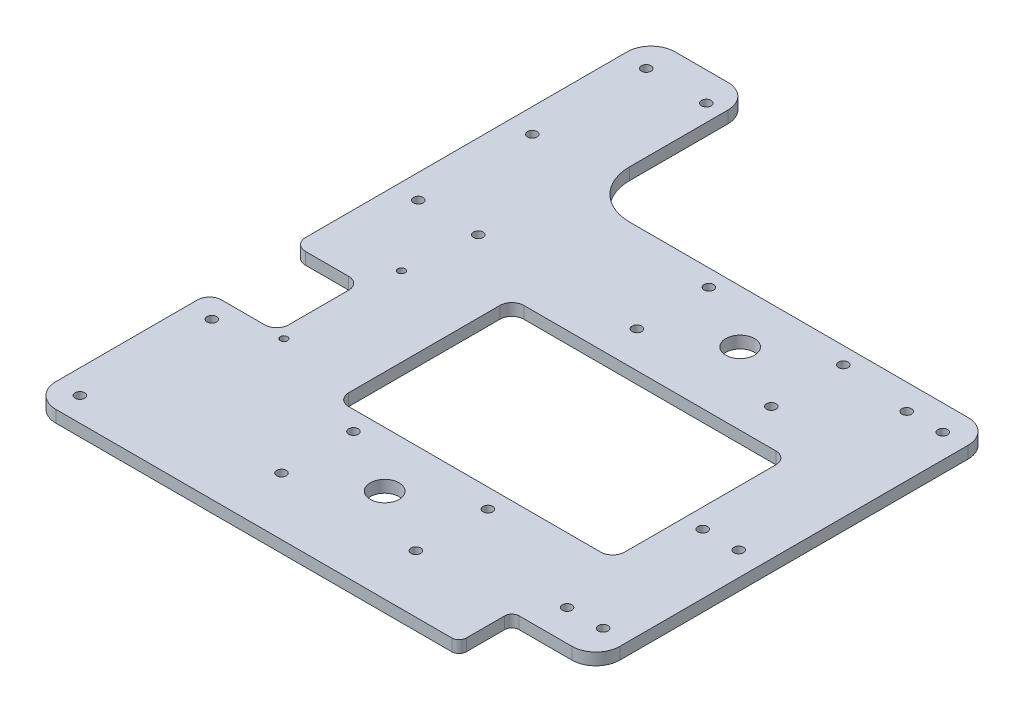
SolidWorks part; units mm, degrees
ref_plane "前视基准面" through (0, 0, 0) normal (0, 0, 1) x (1, 0, 0)
ref_plane "上视基准面" through (0, 0, 0) normal (0, 1, 0) x (1, 0, 0)
ref_plane "右视基准面" through (0, 0, 0) normal (1, 0, 0) x (0, 0, -1)
sketch "草图1" plane through (0, 0, 0) normal (0, 1, 0) x (1, 0, 0)
  line L1 (106.5, -100) -> (-106.5, -100)
  line L2 (106.5, -100) -> (106.5, 100)
  line L3 (106.5, 100) -> (-106.5, 100)
  line L4 (-106.5, -100) -> (-106.5, 100)
  line L5 (106.5, -100) -> (-106.5, 100) construction
  line L6 (106.5, 100) -> (-106.5, -100) construction
  point P0 (0, 0)
  dimension "D1" = 213
  dimension "D2" = 200
extrude "凸台-拉伸1" add sketch "草图1" along normal blind 5
sketch "草图2" plane through (0, 5, 0) normal (0, 1, 0) x (1, 0, 0)
  line L2 (106.5, 100) -> (-106.5, 100) construction
  line L4 (-106.5, 100) -> (-106.5, -100) construction
  circle A0 centre (-4.5, 93) radius 2
  circle A1 centre (51.5, 93) radius 2
  circle A2 centre (-4.5, 63) radius 2
  circle A3 centre (51.5, 63) radius 2
  circle A4 centre (-26.5, -33.0952) radius 2
  circle A5 centre (29.5, -33.0952) radius 2
  circle A6 centre (29.5, -63.0952) radius 2
  circle A7 centre (-26.5, -63.0952) radius 2
  circle A8 centre (1.5, -48.0952) radius 6
  circle A9 centre (23.5, 78) radius 6
  dimension "D2" = 28
  dimension "D3" = 56
  dimension "D4" = 56
  dimension "D5" = 15
  dimension "D6" = 30
  dimension "D7" = 15
  dimension "D8" = 30
  dimension "D9" = 4
  dimension "D10" = 4
  dimension "D11" = 4
  dimension "D12" = 4
  dimension "D13" = 4
  dimension "D14" = 4
  dimension "D15" = 4
  dimension "D16" = 4
  dimension "D17" = 56
  dimension "D18" = 56
  dimension "D19" = 30
  dimension "D20" = 30
  dimension "D21" = 28
  dimension "D22" = 15
  dimension "D23" = 12
  dimension "D24" = 12
  dimension "D25" = 22
  dimension "D26" = 108
  dimension "D27" = 128
  dimension "D28" = 130
  dimension "D29" = 28
  dimension "D30" = 28
  dimension "D31" = 15
extrude "切除-拉伸1" cut sketch "草图2" against normal through all
sketch "草图3" plane through (0, 5, 0) normal (0, 1, 0) x (1, 0, 0)
  line L0 (-106.5, -87.0952) -> (106.5, -87.0952)
  line L1 (-106.5, 100) -> (-106.5, -100) construction
  line L2 (106.5, -100) -> (106.5, 100) construction
  line L3 (106.5, -87.0952) -> (106.5, -100)
  line L4 (106.5, -100) -> (-106.5, -100)
  line L5 (-106.5, -100) -> (-106.5, -87.0952)
  circle A0 centre (1.5, -48.0952) radius 6 construction
  dimension "D1" = 39
extrude "切除-拉伸2" cut sketch "草图3" against normal through all
sketch "草图4" plane through (0, 5, 0) normal (0, 1, 0) x (1, 0, 0)
  line L0 (-106.5, 21.9048) -> (-78.5, 21.9048)
  line L1 (-106.5, 100) -> (-106.5, -87.0952) construction
  line L2 (-78.5, 21.9048) -> (-78.5, -13.0952)
  line L3 (-78.5, -13.0952) -> (-106.5, -13.0952)
  line L4 (-106.5, -13.0952) -> (-106.5, 21.9048)
  line L5 (106.5, -87.0952) -> (-106.5, -87.0952) construction
  dimension "D1" = 74
  dimension "D2" = 109
  dimension "D3" = 28
extrude "切除-拉伸3" cut sketch "草图4" against normal through all
fillet "圆角1" radius 5 4 edges at (-106.5, 2.5, 13.0952) (-78.5, 2.5, 13.0952) (-78.5, 2.5, -21.9048) (-106.5, 2.5, -21.9048)
sketch "草图5" plane through (0, 5, 0) normal (0, 1, 0) x (1, 0, 0)
  line L0 (-106.5, 100) -> (-106.5, 170.9048)
  line L1 (-106.5, 170.9048) -> (-64.5, 170.9048)
  line L2 (-64.5, 170.9048) -> (-64.5, 100)
  line L3 (106.5, 100) -> (-106.5, 100) construction
  line L4 (-106.5, 100) -> (-64.5, 100)
  line L5 (106.5, -87.0952) -> (-106.5, -87.0952) construction
  dimension "D1" = 258
  dimension "D2" = 42
extrude "凸台-拉伸2" add sketch "草图5" against normal blind 5
fillet "圆角2" radius 20 1 edges at (-64.5, 2.5, -100)
sketch "草图6" plane through (0, 5, 0) normal (0, 1, 0) x (1, 0, 0)
  line L0 (-64.5, 170.9048) -> (-106.5, 170.9048) construction
  line L1 (-106.5, 170.9048) -> (-106.5, 26.9048) construction
  circle A0 centre (-96.5, 158.9048) radius 2
  circle A1 centre (-71.5, 158.9048) radius 2
  circle A2 centre (-71.5, 63.9048) radius 2
  circle A3 centre (-96.5, 63.9048) radius 2
  dimension "D1" = 12
  dimension "D2" = 12
  dimension "D3" = 4
  dimension "D4" = 10
  dimension "D5" = 25
  dimension "D6" = 10
  dimension "D7" = 25
  dimension "D8" = 95
  dimension "D9" = 95
  dimension "D10" = 4
  dimension "D11" = 4
  dimension "D12" = 4
extrude "切除-拉伸4" cut sketch "草图6" against normal through all
sketch "草图7" plane through (0, 5, 0) normal (0, 1, 0) x (1, 0, 0)
  line L0 (-106.5, 170.9048) -> (-106.5, 26.9048) construction
  line L1 (-106.5, -18.0952) -> (-106.5, -87.0952) construction
  line L2 (106.5, -87.0952) -> (106.5, 100) construction
  line L3 (106.5, -87.0952) -> (-106.5, -87.0952) construction
  circle A0 centre (-96.5, 111.4048) radius 2
  circle A1 centre (-96.5, -22.0952) radius 2
  circle A2 centre (-96.5, -77.0952) radius 2
  circle A3 centre (96.5, -52.0952) radius 2
  circle A4 centre (96.5, 4.4048) radius 2
  circle A5 centre (96.5, 89.4048) radius 2
  circle A6 centre (81.5, 89.4048) radius 2
  circle A7 centre (81.5, 4.4048) radius 2
  circle A8 centre (81.5, -52.0952) radius 2
  dimension "D1" = 10
  dimension "D2" = 10
  dimension "D3" = 10
  dimension "D4" = 10
  dimension "D5" = 10
  dimension "D6" = 10
  dimension "D7" = 25
  dimension "D8" = 25
  dimension "D9" = 25
  dimension "D10" = 10
  dimension "D11" = 65
  dimension "D12" = 198.5
  dimension "D13" = 35
  dimension "D14" = 35
  dimension "D15" = 91.5
  dimension "D16" = 91.5
  dimension "D17" = 176.5
  dimension "D18" = 176.5
  dimension "D19" = 4
  dimension "D20" = 4
  dimension "D21" = 4
  dimension "D22" = 4
  dimension "D23" = 4
  dimension "D24" = 4
  dimension "D25" = 4
  dimension "D26" = 4
  dimension "D27" = 4
extrude "切除-拉伸5" cut sketch "草图7" against normal through all
sketch "草图8" plane through (0, 5, 0) normal (0, 1, 0) x (1, 0, 0)
  line L0 (71.5, -87.0952) -> (71.5, -65.0952)
  line L1 (106.5, -87.0952) -> (-106.5, -87.0952) construction
  line L2 (71.5, -65.0952) -> (91.5, -65.0952)
  line L3 (91.5, -65.0952) -> (91.5, -87.0952)
  line L4 (91.5, -87.0952) -> (71.5, -87.0952)
  line L9 (106.5, -87.0952) -> (106.5, 100) construction
  dimension "D1" = 22
  dimension "D4" = 15
  dimension "D5" = 20
extrude "切除-拉伸6" cut sketch "草图8" against normal through all
fillet "圆角3" radius 3 4 edges at (71.5, 2.5, 87.0952) (91.5, 2.5, 87.0952) (91.5, 2.5, 65.0952) (71.5, 2.5, 65.0952)
sketch "草图9" plane through (0, 5, 0) normal (0, 1, 0) x (1, 0, 0)
  line L0 (88.5, -65.0952) -> (106.5, -65.0952)
  line L1 (106.5, -87.0952) -> (106.5, 100) construction
  line L2 (106.5, -65.0952) -> (106.5, -87.0952)
  line L3 (106.5, -87.0952) -> (88.5, -87.0952)
  line L4 (88.5, -87.0952) -> (88.5, -65.0952)
extrude "切除-拉伸7" cut sketch "草图9" against normal through all
sketch "草图10" plane through (0, 5, 0) normal (0, 1, 0) x (1, 0, 0)
  line L0 (-106.5, -18.0952) -> (-106.5, -87.0952) construction
  line L1 (-106.5, 170.9048) -> (-106.5, 26.9048) construction
  line L5 (-83.5, 21.9048) -> (-101.5, 21.9048) construction
  circle A0 centre (-74.5, 34.9048) radius 1.5
  circle A1 centre (-74.5, -14.0952) radius 1.5
  dimension "D1" = 49
  dimension "D2" = 32
  dimension "D3" = 32
  dimension "D4" = 36
  dimension "D5" = 3
  dimension "D6" = 3
extrude "切除-拉伸8" cut sketch "草图10" against normal through all
fillet "圆角4" radius 10 5 edges at (-106.5, 2.5, 87.0952) (-106.5, 2.5, -170.9048) (-64.5, 2.5, -170.9048) (106.5, 2.5, -100) (106.5, 2.5, 65.0952)
sketch "草图11" plane through (0, 5, 0) normal (0, 1, 0) x (1, 0, 0)
  line L0 (-41.5, 47.9048) -> (73.5, 47.9048)
  line L1 (73.5, 47.9048) -> (73.5, -25.0952)
  line L2 (73.5, -25.0952) -> (-41.5, -25.0952)
  line L3 (-41.5, -25.0952) -> (-41.5, 47.9048)
  line L4 (-106.5, 160.9048) -> (-106.5, 26.9048) construction
  line L5 (68.5, -87.0952) -> (-96.5, -87.0952) construction
  dimension "D1" = 65
  dimension "D2" = 180
  dimension "D3" = 62
  dimension "D4" = 135
extrude "切除-拉伸9" cut sketch "草图11" against normal through all
fillet "圆角5" radius 5 4 edges at (-41.5, 2.5, 25.0952) (-41.5, 2.5, -47.9048) (73.5, 2.5, -47.9048) (73.5, 2.5, 25.0952)
